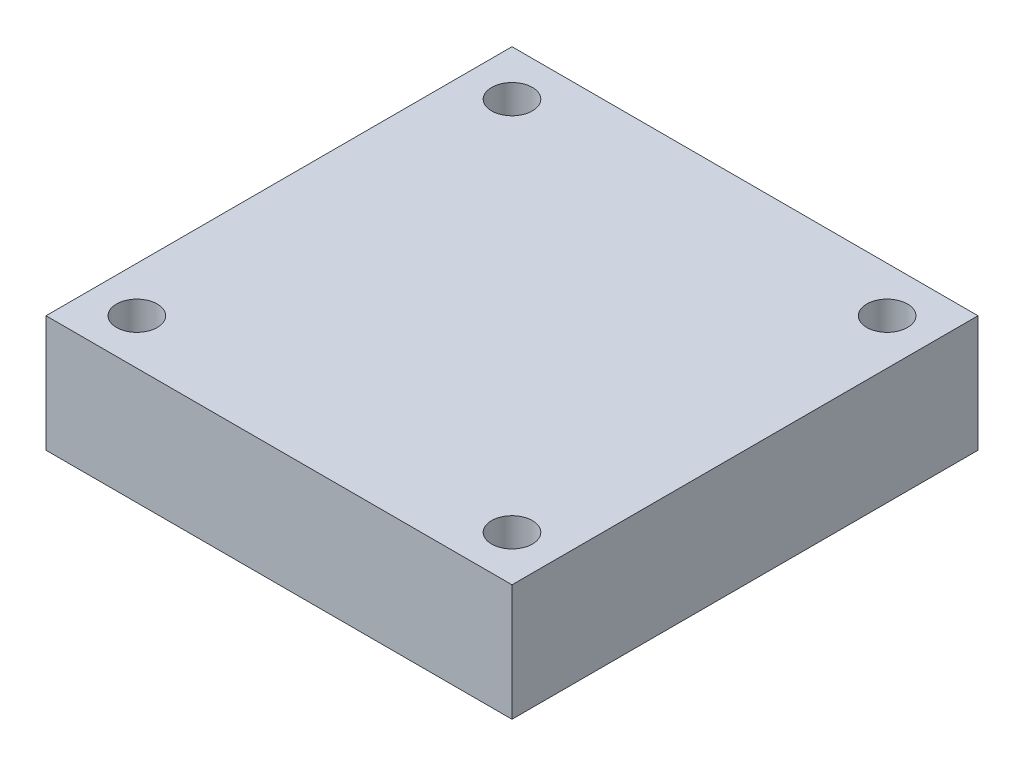
SolidWorks part; units mm, degrees
material "AISI 1035 Steel (SS)"
ref_plane "Front Plane" through (0, 0, 0) normal (0, 0, 1) x (1, 0, 0)
ref_plane "Top Plane" through (0, 0, 0) normal (0, 1, 0) x (1, 0, 0)
ref_plane "Right Plane" through (0, 0, 0) normal (1, 0, 0) x (0, 0, -1)
sketch "Sketch1" plane through (0, 0, 0) normal (0, 1, 0) x (1, 0, 0)
  line L1 (0, 0) -> (40, 0)
  line L2 (0, 0) -> (0, -40)
  line L3 (0, -40) -> (40, -40)
  line L4 (40, 0) -> (40, -40)
  dimension "D1" = 40
  dimension "D2" = 40
extrude "Boss-Extrude1" add sketch "Sketch1" along normal blind 10
sketch "Sketch2" plane through (0, 10, 0) normal (0, 1, 0) x (1, 0, 0)
  line L0 (0, 0) -> (0, -40) construction
  line L1 (40, 0) -> (0, 0) construction
  circle A0 centre (3.9, -3.9) radius 1.75
  circle A1 centre (36.1, -3.9) radius 1.75
  circle A2 centre (36.1, -36.1) radius 1.75
  circle A3 centre (3.9, -36.1) radius 1.75
  dimension "D1" = 3.5
  dimension "D2" = 3.9
  dimension "D3" = 3.9
  dimension "D4" = 2
  dimension "D5" = 2
extrude "Cut-Extrude1" cut sketch "Sketch2" against normal blind 10
equation "\"D2@Sketch2\"=20-32.2/2"
equation "\"D3@Sketch2\"=\"D2@Sketch2\""
